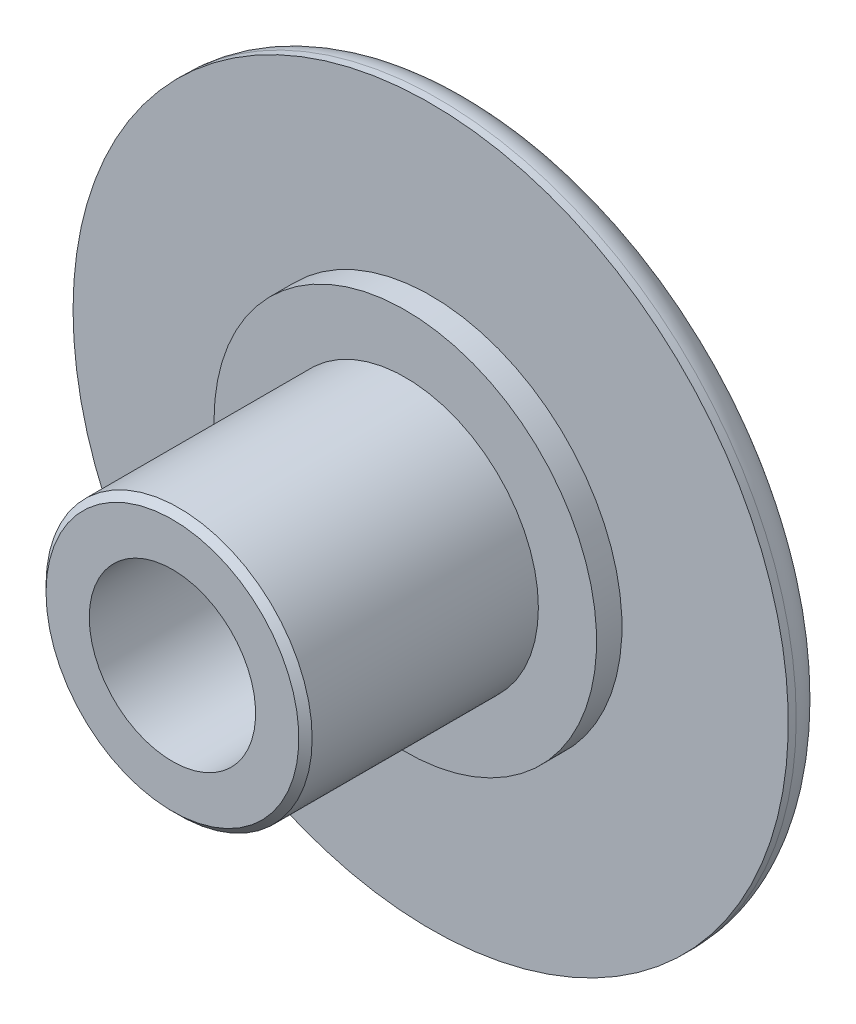
SolidWorks part; units mm, degrees
ref_plane "Front Plane" through (0, 0, 0) normal (0, 0, 1) x (1, 0, 0)
ref_plane "Top Plane" through (0, 0, 0) normal (0, 1, 0) x (1, 0, 0)
ref_plane "Right Plane" through (0, 0, 0) normal (1, 0, 0) x (0, 0, -1)
sketch "Sketch1" plane through (0, 0, 0) normal (0, 1, 0) x (1, 0, 0)
  line L0 (0, 9.8659) -> (0, 0) construction
  line L1 (0, 0) -> (11.1039, 0) construction
  line L2 (4, 0) -> (2.5, 0)
  line L3 (2.5, 0) -> (2.5, 6)
  line L4 (2.5, 6) -> (0, 6)
  line L5 (0, 6) -> (0, 9)
  line L6 (0, 9) -> (10.75, 9)
  line L7 (10.75, 9) -> (10.75, 7.7622)
  line L8 (10.75, 7.7622) -> (5.75, 7.7622)
  line L9 (5.75, 7.7622) -> (5.75, 7)
  line L10 (5.75, 7) -> (4, 7)
  line L11 (4, 7) -> (4, 0)
  dimension "D1" = 9
  dimension "D2" = 6
  dimension "D3" = 2
  dimension "D4" = 0.7622
  dimension "D5" = 1.5
  dimension "D6" = 4
  dimension "D7" = 10.75
  dimension "D8" = 5.75
revolve "Revolve1" add sketch "Sketch1" angle 360 about L0
chamfer "Chamfer3" distance 0.2 angle 45 1 edges at (-4, 0, 0)
fillet "Fillet2" radius 1 1 edges at (-10.75, 0, -9)
